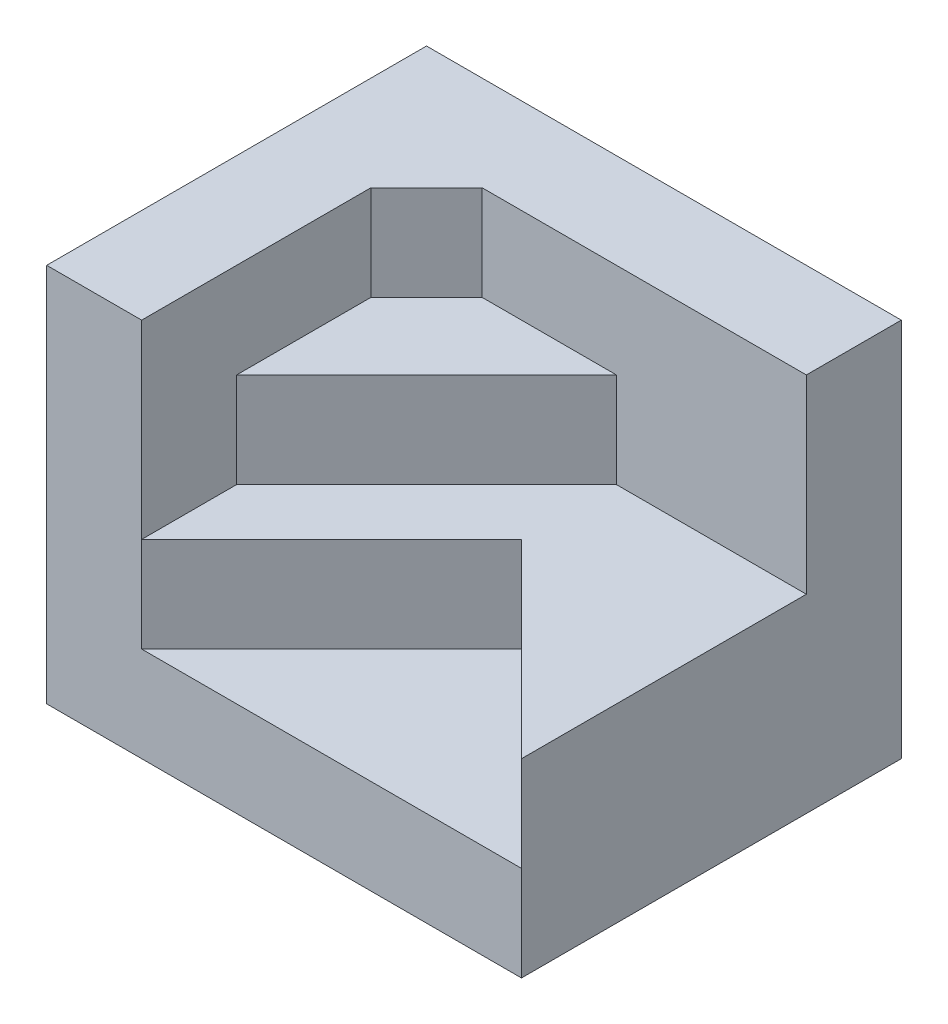
SolidWorks part; units mm, degrees
ref_plane "Front Plane" through (0, 0, 0) normal (0, 0, 1) x (1, 0, 0)
ref_plane "Top Plane" through (0, 0, 0) normal (0, 1, 0) x (1, 0, 0)
ref_plane "Right Plane" through (0, 0, 0) normal (1, 0, 0) x (0, 0, -1)
sketch "Sketch1" plane through (0, 0, 0) normal (0, 1, 0) x (1, 0, 0)
  line L1 (-40, 20) -> (10, 20)
  line L2 (-40, 20) -> (-40, -20)
  line L3 (-40, -20) -> (10, -20)
  line L4 (10, 20) -> (10, -20)
  point P0 (0, 0)
  dimension "D1" = 40
  dimension "D2" = 50
extrude "Boss-Extrude1" add sketch "Sketch1" along normal blind 40 contours L2 L3 L4 L1
sketch "Sketch2" plane through (0, 40, 0) normal (0, 1, 0) x (1, 0, 0)
  line L3 (-30, -10) -> (-30, 4.1421)
  line L4 (-24.1421, 10) -> (-10, 10)
  line L8 (-10, 10) -> (-30, -10)
  line L9 (-24.1421, 10) -> (-30, 4.1421)
  dimension "D5" = 10
extrude "Cut-Extrude1" cut sketch "Sketch2" against normal blind 10
sketch "Sketch3" plane through (0, 40, 0) normal (0, 1, 0) x (1, 0, 0)
  line L0 (-30, -10) -> (-30, -20)
  line L1 (-40, -20) -> (10, -20) construction
  line L2 (-10, 10) -> (10, 10)
  line L3 (10, 20) -> (10, -20) construction
  line L4 (10, 10) -> (10, -20)
  line L5 (10, -20) -> (-30, -20)
  line L6 (-10, 10) -> (-30, -10)
extrude "Cut-Extrude2" cut sketch "Sketch3" against normal blind 20
sketch "Sketch4" plane through (0, 20, 0) normal (0, 1, 0) x (1, 0, 0)
  line L0 (-30, -20) -> (-10, 0)
  line L1 (-10, 0) -> (10, -20)
  line L2 (10, -20) -> (-30, -20)
  dimension "D1" = 45
  dimension "D2" = 20
extrude "Cut-Extrude3" cut sketch "Sketch4" against normal blind 10
